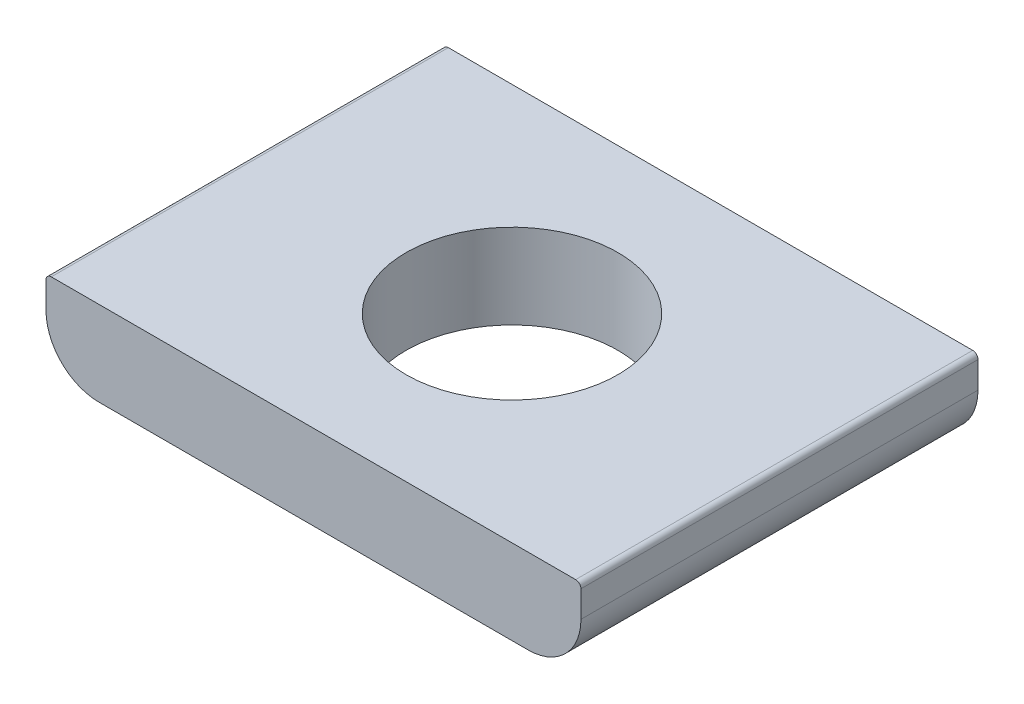
SolidWorks part; units mm, degrees
ref_plane "Front Plane" through (0, 0, 0) normal (0, 0, 1) x (1, 0, 0)
ref_plane "Top Plane" through (0, 0, 0) normal (0, 1, 0) x (1, 0, 0)
ref_plane "Right Plane" through (0, 0, 0) normal (1, 0, 0) x (0, 0, -1)
sketch "Sketch1" plane through (0, 0, 0) normal (0, 0, 1) x (1, 0, 0)
  line L0 (9.905, 0) -> (-9.905, 0)
  line L1 (-10.105, -0.2) -> (-10.105, -1.2)
  line L2 (-8.105, -3.2) -> (8.105, -3.2)
  line L3 (0, 4.0324) -> (0, -6.3482) construction
  line L4 (10.105, -0.2) -> (10.105, -1.2)
  arc A0 (-9.905, 0) -> (-10.105, -0.2) centre (-9.905, -0.2) ccw
  arc A1 (-8.105, -3.2) -> (-10.105, -1.2) centre (-8.105, -1.2) cw
  arc A2 (8.105, -3.2) -> (10.105, -1.2) centre (8.105, -1.2) ccw
  arc A3 (9.905, 0) -> (10.105, -0.2) centre (9.905, -0.2) cw
  point P5 (0, 0)
  point P7 (-10.105, 0)
  point P10 (-10.105, -3.2)
  point P19 (0, -3.2)
  dimension "D2" = 0.2
  dimension "D4" = 2
  dimension "D1" = 10.105
  dimension "D3" = 3
extrude "Boss-Extrude1" add sketch "Sketch1" along normal blind 15
hole_wizard "Ø8.0mm Dowel Hole1" positions "Sketch2" profile "Sketch3" hole size "Ø8.0" standard "DIN" end condition through all
sketch "Sketch2" plane through (0, 0, 0) normal (0, 1, 0) x (1, 0, 0)
  point P0 (0, -7.5)
sketch "Sketch3" plane through (0, 0, 7.5) normal (1, 0, 0) x (0, 0, 1)
  line L0 (0, 0) -> (0, 3.2)
  line L1 (0, 3.2) -> (4, 3.2)
  line L2 (4, 3.2) -> (4, 0)
  line L5 (4, 0) -> (0, 0)
  line L11 (0, -6.35) -> (0, 107.95) construction
  dimension "Thru Hole Dia." = 8
  dimension "Thru Hole Depth" = 3.2
